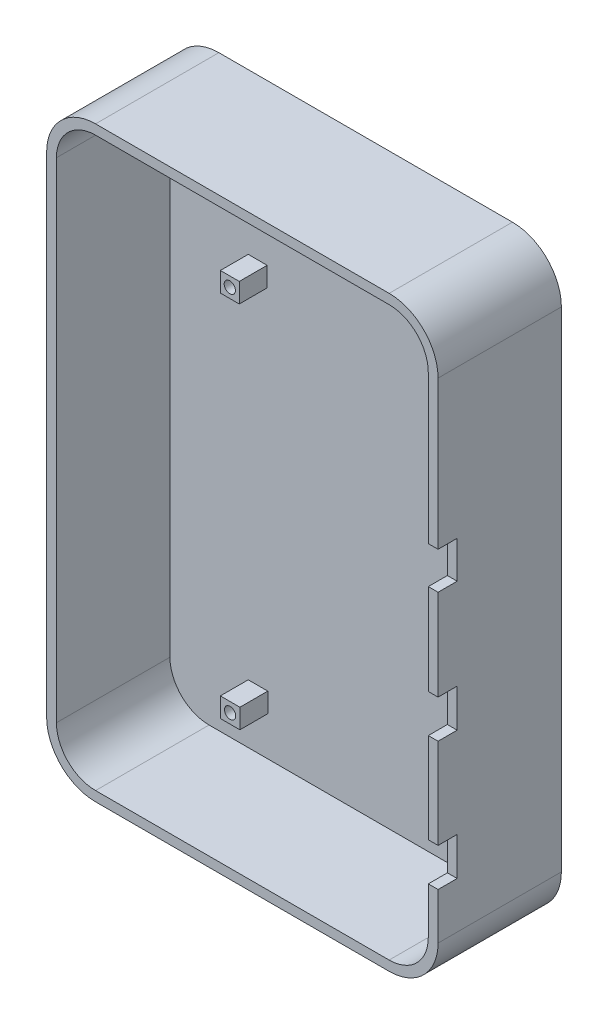
SolidWorks part; units mm, degrees
ref_plane "Plan de face" through (0, 0, 0) normal (0, 0, 1) x (1, 0, 0)
ref_plane "Plan de dessus" through (0, 0, 0) normal (0, 1, 0) x (1, 0, 0)
ref_plane "Plan de droite" through (0, 0, 0) normal (1, 0, 0) x (0, 0, -1)
sketch "Esquisse1" plane through (0, 0, 0) normal (0, 0, 1) x (1, 0, 0)
  line L1 (0, 0) -> (-80, 0)
  line L2 (0, 0) -> (0, 120)
  line L3 (0, 120) -> (-80, 120)
  line L4 (-80, 0) -> (-80, 120)
  circle A0 centre (-70, 110) radius 10
  circle A1 centre (-10, 110) radius 10
  circle A2 centre (-70, 10) radius 10
  circle A3 centre (-10, 10) radius 10
  dimension "D3" = 20
  dimension "D4" = 20
  dimension "D5" = 20
  dimension "D1" = 120
  dimension "D2" = 80
extrude "Boss.-Extru.3" add sketch "Esquisse1" along normal blind 2 contours A3 L2 A1 L3 A0 L4 A2 L1 | A0 | A1 | A3 | A2
sketch "Esquisse3" plane through (0, 0, 2) normal (0, 0, 1) x (1, 0, 0)
  line L0 (-10, 120) -> (-70, 120) construction
  line L1 (-2, 2) -> (-78, 2)
  line L2 (-2, 2) -> (-2, 118)
  line L3 (-2, 118) -> (-78, 118)
  line L4 (-78, 2) -> (-78, 118)
  line L5 (0, 10) -> (0, 110) construction
  line L6 (-10, 0) -> (-70, 0) construction
  line L7 (-80, 10) -> (-80, 110) construction
  circle A0 centre (-70, 110) radius 10
  circle A1 centre (-10, 110) radius 10
  circle A2 centre (-10, 10) radius 10
  circle A3 centre (-70, 10) radius 10
  circle A4 centre (-10, 110) radius 8
  circle A5 centre (-70, 110) radius 8
  circle A6 centre (-70, 10) radius 8
  circle A7 centre (-10, 10) radius 8
  line M6 (-70, 0) -> (-10, 0)
  arc M7 (-10, 0) -> (0, 10) centre (-10, 10) ccw
  line M8 (0, 10) -> (0, 110)
  arc M9 (0, 110) -> (-10, 120) centre (-10, 110) ccw
  line M10 (-10, 120) -> (-70, 120)
  arc M11 (-70, 120) -> (-80, 110) centre (-70, 110) ccw
  line M12 (-80, 110) -> (-80, 10)
  arc M13 (-80, 10) -> (-70, 0) centre (-70, 10) ccw
  dimension "D1" = 2
  dimension "D2" = 2
  dimension "D3" = 2
  dimension "D4" = 2
extrude "Boss.-Extru.4" add sketch "Esquisse3" along normal blind 19.3 contours L4 A3 M13 | A6 L4 L1 M13 | A3 L1 M13 | A3 A2 L1 M6 | A3 L4 A0 M12 | A0 L4 M11 | A5 L3 L4 M11 | L3 A0 M11 | A1 A0 L3 M10 | A1 L3 M9 | A4 L2 L3 M9 | L2 A1 M9 | A2 A1 L2 M8 | A2 L2 M7 | A7 L1 L2 M7 | L1 A2 M7
sketch "Esquisse4" plane through (0, 0, 21.3) normal (0, 0, 1) x (1, 0, 0)
  line L0 (-2, 10) -> (-2, 19.485) construction
  line L1 (-2, 10) -> (-2, 110) construction
  line L2 (-2, 19.485) -> (-2, 27.285) construction
  line L3 (-2, 27.285) -> (-2, 45.735) construction
  line L4 (-2, 45.735) -> (-2, 53.535) construction
  line L5 (-2, 10) -> (-2, 110) construction
  line L6 (-2, 53.535) -> (-2, 72.1) construction
  line L7 (-2, 72.1) -> (-2, 79.7) construction
  line L8 (-2, 79.7) -> (-2, 110) construction
  line L9 (-2, 79.7) -> (0, 79.7)
  line L10 (0, 10) -> (0, 110) construction
  line L11 (-2, 79.7) -> (-2, 72.1)
  line L12 (-2, 72.1) -> (0, 72.1)
  line L13 (0, 72.1) -> (0, 79.7)
  line L14 (-2, 53.535) -> (0, 53.535)
  line L15 (-2, 53.535) -> (-2, 45.735)
  line L16 (-2, 45.735) -> (0, 45.735)
  line L17 (0, 45.735) -> (0, 53.535)
  line L18 (-2, 27.285) -> (-2, 19.485)
  line L19 (-2, 19.485) -> (0, 19.485)
  line L20 (0, 19.485) -> (0, 27.285)
  line L21 (0, 27.285) -> (-2, 27.285)
  line L22 (-10, 120) -> (-70, 120) construction
  line L23 (0, 0) -> (-80, 0)
  line L24 (0, 0) -> (0, 120)
  line L25 (0, 120) -> (-80, 120)
  line L26 (-80, 0) -> (-80, 120)
  line L27 (-80, 110) -> (-80, 10) construction
  circle A0 centre (-70, 110) radius 10
  circle A1 centre (-10, 110) radius 10
  circle A2 centre (-10, 10) radius 10
  circle A3 centre (-70, 10) radius 10
  circle A4 centre (-70, 10) radius 8
  circle A5 centre (-10, 10) radius 8
  circle A6 centre (-10, 110) radius 8
  circle A7 centre (-70, 110) radius 8
  line M1 (0, 10) -> (0, 110)
  arc M2 (0, 110) -> (-10, 120) centre (-10, 110) ccw
  line M3 (-10, 120) -> (-70, 120)
  arc M4 (-70, 120) -> (-80, 110) centre (-70, 110) ccw
  line M5 (-80, 110) -> (-80, 10)
  arc M6 (-80, 10) -> (-70, 0) centre (-70, 10) ccw
  line M7 (-70, 0) -> (-10, 0)
  arc M8 (-10, 0) -> (0, 10) centre (-10, 10) ccw
  line M9 (-78, 10) -> (-78, 110)
  arc M10 (-78, 110) -> (-70, 118) centre (-70, 110) cw
  line M11 (-70, 118) -> (-10, 118)
  arc M12 (-10, 118) -> (-2, 110) centre (-10, 110) cw
  line M13 (-2, 110) -> (-2, 10)
  arc M14 (-2, 10) -> (-10, 2) centre (-10, 10) cw
  line M15 (-10, 2) -> (-70, 2)
  arc M16 (-70, 2) -> (-78, 10) centre (-70, 10) cw
  dimension "D1" = 9.485
  dimension "D2" = 7.8
  dimension "D3" = 18.45
  dimension "D4" = 7.8
  dimension "D5" = 18.565
  dimension "D6" = 7.6
  dimension "D7" = 0
  dimension "D8" = 0
extrude "Boss.-Extru.5" add sketch "Esquisse4" along normal blind 3.9 contours A1 A0 M3 M11 | A0 M11 M4 M9 M10 | A1 M2 M11 M12 M13 | A1 L9 M13 M1 | L14 L12 M13 M1 | L21 L16 M1 M13 | A2 L19 M1 M13 | A2 M8 M13 M14 M15 | A3 A2 M7 M15 | A3 M9 M6 M15 M16 | A3 A0 M9 M5
sketch "Esquisse5" plane through (0, 0, 2) normal (0, 0, 1) x (1, 0, 0)
  line L0 (-2, 10) -> (-4, 10) construction
  line L1 (-4, 10) -> (-4, 12) construction
  line L2 (-6, 10) -> (-58, 10) construction
  line L3 (-2, 10) -> (-6, 10)
  line L4 (-2, 10) -> (-2, 14)
  line L5 (-2, 14) -> (-6, 14)
  line L6 (-6, 10) -> (-6, 14)
  line L7 (-62, 14) -> (-58, 10) construction
  line L8 (-58, 10) -> (-62, 10)
  line L9 (-58, 10) -> (-58, 14)
  line L10 (-58, 14) -> (-62, 14)
  line L11 (-62, 10) -> (-62, 14)
  line L12 (-62, 14) -> (-62, 85.3) construction
  line L13 (-62, 85.3) -> (-58.13, 89.3) construction
  line L14 (-62, 85.3) -> (-58.13, 85.3)
  line L15 (-62, 85.3) -> (-62, 89.3)
  line L16 (-62, 89.3) -> (-58.13, 89.3)
  line L17 (-58.13, 85.3) -> (-58.13, 89.3)
  line L18 (-58.13, 89.3) -> (-6, 89.3) construction
  line L19 (-6, 89.3) -> (-2, 86) construction
  line L20 (-6, 89.3) -> (-2, 89.3)
  line L21 (-6, 89.3) -> (-6, 86)
  line L22 (-6, 86) -> (-2, 86)
  line L23 (-2, 89.3) -> (-2, 86)
  line L24 (-2, 110) -> (-2, 79.7) construction
  circle A0 centre (-4, 12) radius 1.15
  circle A1 centre (-60, 12) radius 1.15
  circle A2 centre (-60.065, 87.3) radius 1.15
  circle A3 centre (-4, 87.65) radius 1.15
  dimension "D3" = 2.3
  dimension "D9" = 2.3
  dimension "D12" = 2.3
  dimension "D15" = 2.3
  dimension "D1" = 2
  dimension "D2" = 2
  dimension "D4" = 4
  dimension "D5" = 4
  dimension "D6" = 4
  dimension "D7" = 4
  dimension "D8" = 60
  dimension "D10" = 4
  dimension "D11" = 79.3
  dimension "D13" = 4
  dimension "D14" = 0
extrude "Boss.-Extru.6" add sketch "Esquisse5" along normal blind 5.7
